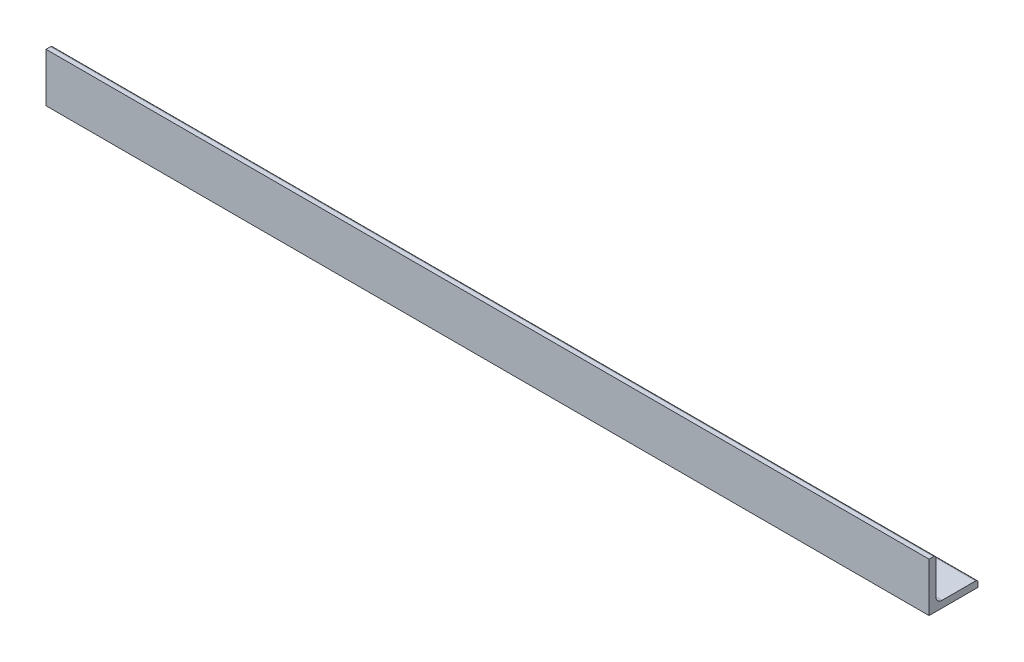
SolidWorks part; units mm, degrees
material "ASTM A36 Acero"
ref_plane "Alzado" through (0, 0, 0) normal (0, 0, 1) x (1, 0, 0)
ref_plane "Planta" through (0, 0, 0) normal (0, 1, 0) x (1, 0, 0)
ref_plane "Vista lateral" through (0, 0, 0) normal (1, 0, 0) x (0, 0, -1)
sketch "Croquis1" plane through (0, 0, 0) normal (0, 0, 1) x (1, 0, 0)
  line L0 (0, 0) -> (650, 0)
  dimension "D1" = 650
other "L angle (equal) 3.6X5(1)"
ref_plane "Plano1" through (0, 0, 0) normal (1, 0, 0) x (0, 1, 0)
sketch "Sketch1" plane through (0, 0, 0) normal (1, 0, 0) x (0, 1, 0)
  line L0 (36, 0) -> (0, 0)
  line L1 (0, 0) -> (0, -36)
  line L2 (34.3333, -5) -> (9.5, -5)
  line L3 (5, -9.5) -> (5, -34.3333)
  line L4 (36, 0) -> (36, -3.3333)
  line L5 (0, -36) -> (3.3333, -36)
  arc A0 (36, -3.3333) -> (34.3333, -5) centre (34.3333, -3.3333) cw
  arc A1 (3.3333, -36) -> (5, -34.3333) centre (3.3333, -34.3333) ccw
  arc A2 (9.5, -5) -> (5, -9.5) centre (9.5, -9.5) ccw
  point P2 (18, 0)
  point P13 (0, -18)
  point P15 (0, 0)
  dimension "r1" = 1.6667
  dimension "r" = 4.5
  dimension "b" = 36
  dimension "d" = 5
